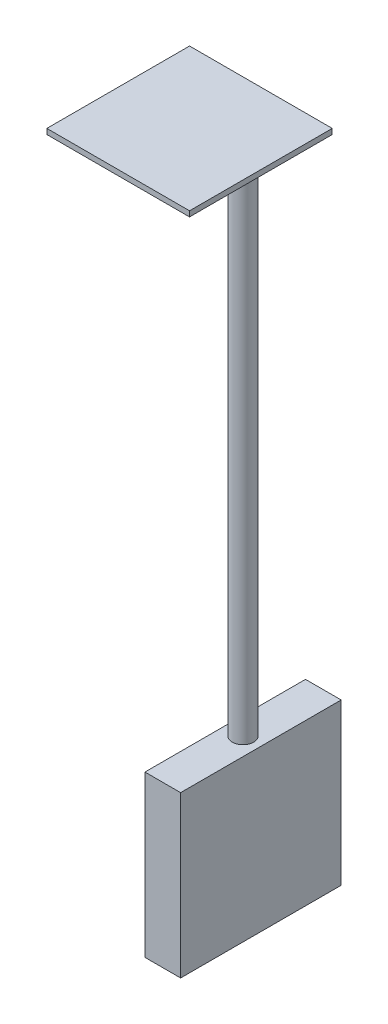
SolidWorks part; units mm, degrees
ref_plane "Plan de face" through (0, 0, 0) normal (0, 0, 1) x (1, 0, 0)
ref_plane "Plan de dessus" through (0, 0, 0) normal (0, 1, 0) x (1, 0, 0)
ref_plane "Plan de droite" through (0, 0, 0) normal (1, 0, 0) x (0, 0, -1)
sketch "Esquisse1" plane through (0, 0, 0) normal (1, 0, 0) x (0, 0, -1)
  line L1 (75.9293, 32.036) -> (-14.0707, 32.036)
  line L2 (75.9293, 32.036) -> (75.9293, -57.964)
  line L3 (75.9293, -57.964) -> (-14.0707, -57.964)
  line L4 (-14.0707, 32.036) -> (-14.0707, -57.964)
  dimension "D1" = 90
  dimension "D2" = 90
extrude "Boss.-Extru.1" add sketch "Esquisse1" along normal blind 20
sketch "Esquisse2" plane through (0, 32.036, 0) normal (0, 1, 0) x (1, 0, 0)
  line L0 (20, 75.9293) -> (20, -14.0707) construction
  line L1 (20, -14.0707) -> (0, -14.0707) construction
  circle A0 centre (10, 30.9293) radius 6
  dimension "D1" = 10
  dimension "D2" = 45
extrude "Boss.-Extru.2" add sketch "Esquisse2" along normal blind 277
sketch "Esquisse3" plane through (0, 309.036, 0) normal (0, 1, 0) x (1, 0, 0)
  line L1 (-60, -9.0707) -> (20, -9.0707)
  line L2 (-60, -9.0707) -> (-60, 70.9293)
  line L3 (-60, 70.9293) -> (20, 70.9293)
  line L4 (20, -9.0707) -> (20, 70.9293)
  circle A0 centre (10, 30.9293) radius 6 construction
  dimension "D4" = 10
  dimension "D1" = 80
  dimension "D2" = 80
  dimension "D3" = 40
extrude "Boss.-Extru.3" add sketch "Esquisse3" along normal blind 2.9
sketch "Esquisse4" plane through (0, 311.936, 0) normal (0, 1, 0) x (1, 0, 0)
  line L1 (-60, 70.9293) -> (20, 70.9293)
  line L2 (-60, 70.9293) -> (-60, -9.0707)
  line L3 (-60, -9.0707) -> (20, -9.0707)
  line L4 (20, 70.9293) -> (20, -9.0707)
extrude "Boss.-Extru.4" add sketch "Esquisse4" along normal blind 0.1
